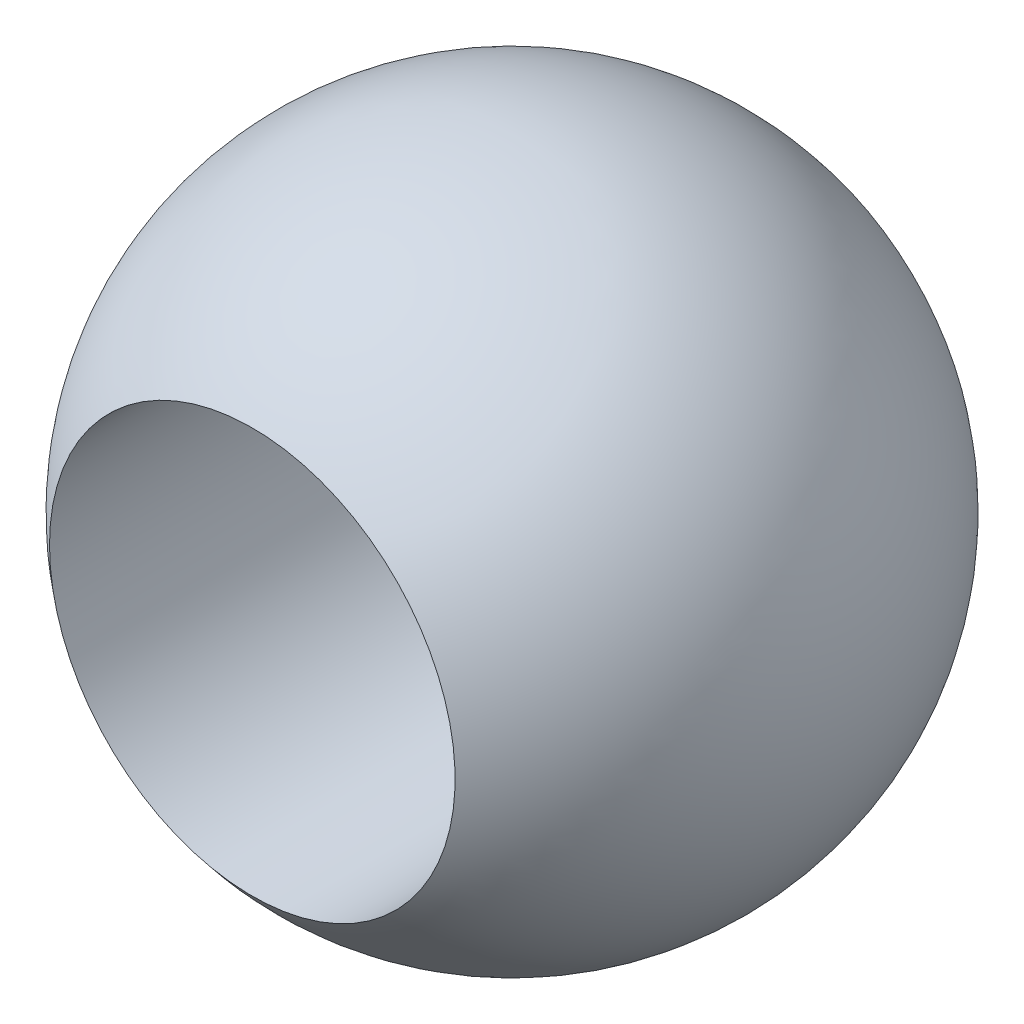
SolidWorks part; units mm, degrees
ref_plane "Ön Düzlem" through (0, 0, 0) normal (0, 0, 1) x (1, 0, 0)
ref_plane "Üst Düzlem" through (0, 0, 0) normal (0, 1, 0) x (1, 0, 0)
ref_plane "Sağ Düzlem" through (0, 0, 0) normal (1, 0, 0) x (0, 0, -1)
sketch "Sketch1" plane through (0, 0, 0) normal (0, 0, 1) x (1, 0, 0)
  line L0 (-6.5, 0) -> (6.5, 0) construction
  line L1 (-6.5, 0) -> (6.5, 0)
  arc A0 (-6.5, 0) -> (6.5, 0) centre (0, 0) ccw
  dimension "D1" = 13
revolve "Revolve1" add sketch "Sketch1" angle 360 about L0
sketch "Sketch3" plane through (0, 0, 0) normal (0, 0, 1) x (1, 0, 0)
  circle A0 centre (0, 0) radius 4
  dimension "D1" = 8
extrude "Cut-Extrude1" cut sketch "Sketch3" against normal mid plane 30
